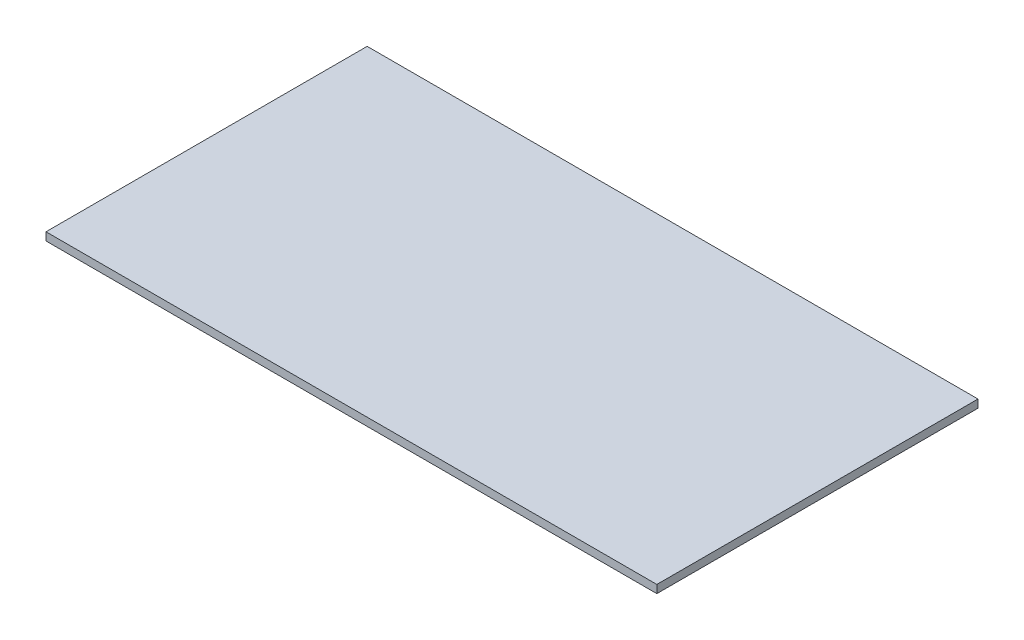
SolidWorks part; units mm, degrees
material "1060 Alloy"
ref_plane "Front Plane" through (0, 0, 0) normal (0, 0, 1) x (1, 0, 0)
ref_plane "Top Plane" through (0, 0, 0) normal (0, 1, 0) x (1, 0, 0)
ref_plane "Right Plane" through (0, 0, 0) normal (1, 0, 0) x (0, 0, -1)
sketch "Sketch1" plane through (0, 0, 0) normal (0, 1, 0) x (1, 0, 0)
  line L1 (0, 0) -> (485, 0)
  line L2 (0, 0) -> (0, 255)
  line L3 (0, 255) -> (485, 255)
  line L4 (485, 0) -> (485, 255)
  dimension "D1" = 485
  dimension "D2" = 255
extrude "Boss-Extrude1" add sketch "Sketch1" along normal blind 6.35
